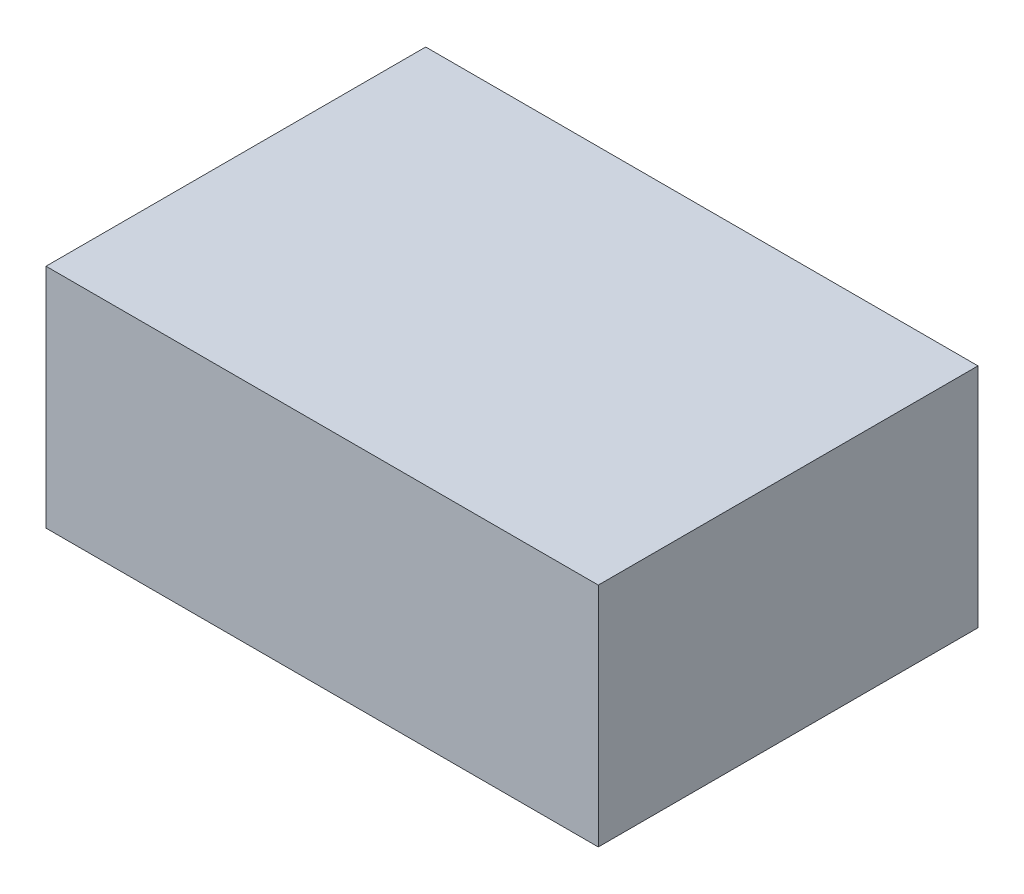
SolidWorks part; units mm, degrees
ref_plane "Front Plane" through (0, 0, 0) normal (0, 0, 1) x (1, 0, 0)
ref_plane "Top Plane" through (0, 0, 0) normal (0, 1, 0) x (1, 0, 0)
ref_plane "Right Plane" through (0, 0, 0) normal (1, 0, 0) x (0, 0, -1)
sketch "Sketch1" plane through (0, 0, 0) normal (0, 0, 1) x (1, 0, 0)
  line L4 (0.05, 0.22) -> (0.05, -0.24)
  line L5 (0.05, -0.24) -> (1.17, -0.24)
  line L6 (1.17, -0.24) -> (1.17, 0.22)
  line L7 (1.17, 0.22) -> (0.05, 0.22)
  line L8 (0.05, 0.22) -> (0.05, -0.24)
  line L9 (0.05, -0.24) -> (1.17, -0.24)
  line L10 (1.17, -0.24) -> (1.17, 0.22)
  line L11 (1.17, 0.22) -> (0.05, 0.22)
  dimension "D1" = 0
extrude "Boss-Extrude1" add sketch "Sketch1" against normal up to surface (0.77 mm away)
